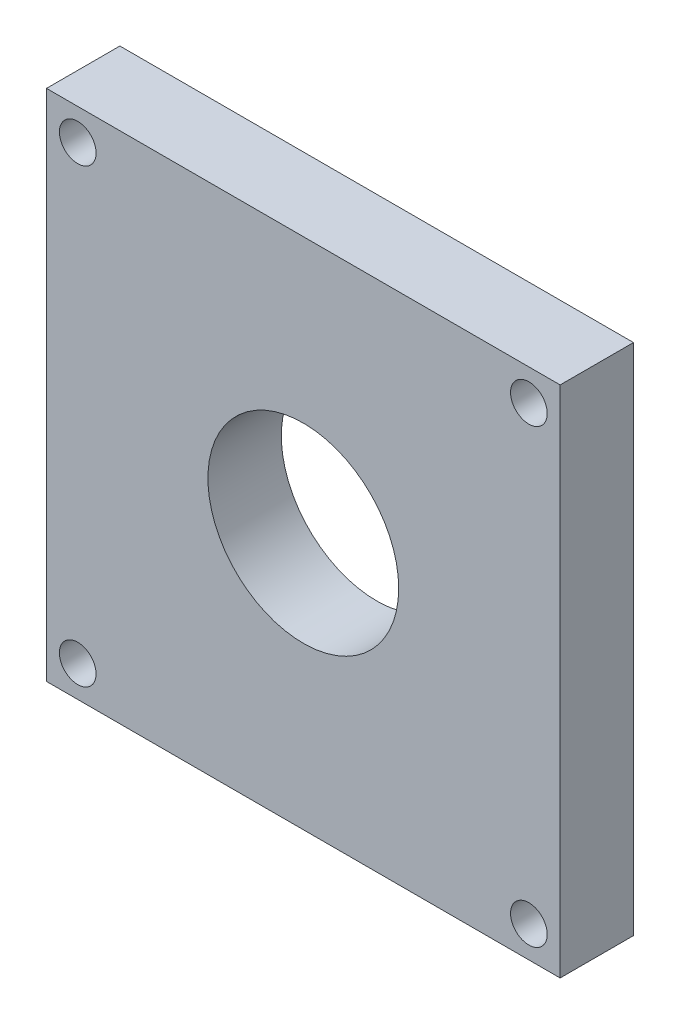
SolidWorks part; units mm, degrees
ref_plane "Alzado" through (0, 0, 0) normal (0, 0, 1) x (1, 0, 0)
ref_plane "Planta" through (0, 0, 0) normal (0, 1, 0) x (1, 0, 0)
ref_plane "Vista lateral" through (0, 0, 0) normal (1, 0, 0) x (0, 0, -1)
sketch "Croquis1" plane through (0, 0, 0) normal (0, 0, 1) x (1, 0, 0)
  line L0 (-17.5, 17.5) -> (-17.5, 13.25) construction
  line L1 (17.5, -17.5) -> (-17.5, -17.5)
  line L2 (17.5, -17.5) -> (17.5, 17.5)
  line L3 (17.5, 17.5) -> (-17.5, 17.5)
  line L4 (-17.5, -17.5) -> (-17.5, 17.5)
  line L5 (17.5, -17.5) -> (-17.5, 17.5) construction
  line L6 (17.5, 17.5) -> (-17.5, -17.5) construction
  line L7 (-17.5, 13.25) -> (-15.37, 13.25) construction
  line L8 (-15.37, 13.25) -> (-15.37, 15.37) construction
  line L9 (17.5, 13.25) -> (15.37, 13.25) construction
  line L10 (15.37, 13.25) -> (15.37, 15.37) construction
  line L11 (15.37, -17.5) -> (15.37, -15.37) construction
  line L12 (-17.5, -15.37) -> (-15.37, -15.37) construction
  circle A0 centre (-15.37, 15.37) radius 1.25
  circle A1 centre (15.37, 15.37) radius 1.25
  circle A2 centre (15.37, -15.37) radius 1.25
  circle A3 centre (-15.37, -15.37) radius 1.25
  circle A4 centre (0, 0) radius 6.5
  point P0 (0, 0)
  dimension "D5" = 2.5
  dimension "D8" = 2.5
  dimension "D10" = 2.5
  dimension "D12" = 2.5
  dimension "D13" = 13
  dimension "D1" = 35
  dimension "D2" = 4.25
  dimension "D3" = 2.13
  dimension "D4" = 2.12
  dimension "D6" = 2.13
  dimension "D7" = 2.12
  dimension "D9" = 2.13
  dimension "D11" = 2.13
extrude "Saliente-Extruir1" add sketch "Croquis1" along normal blind 5
